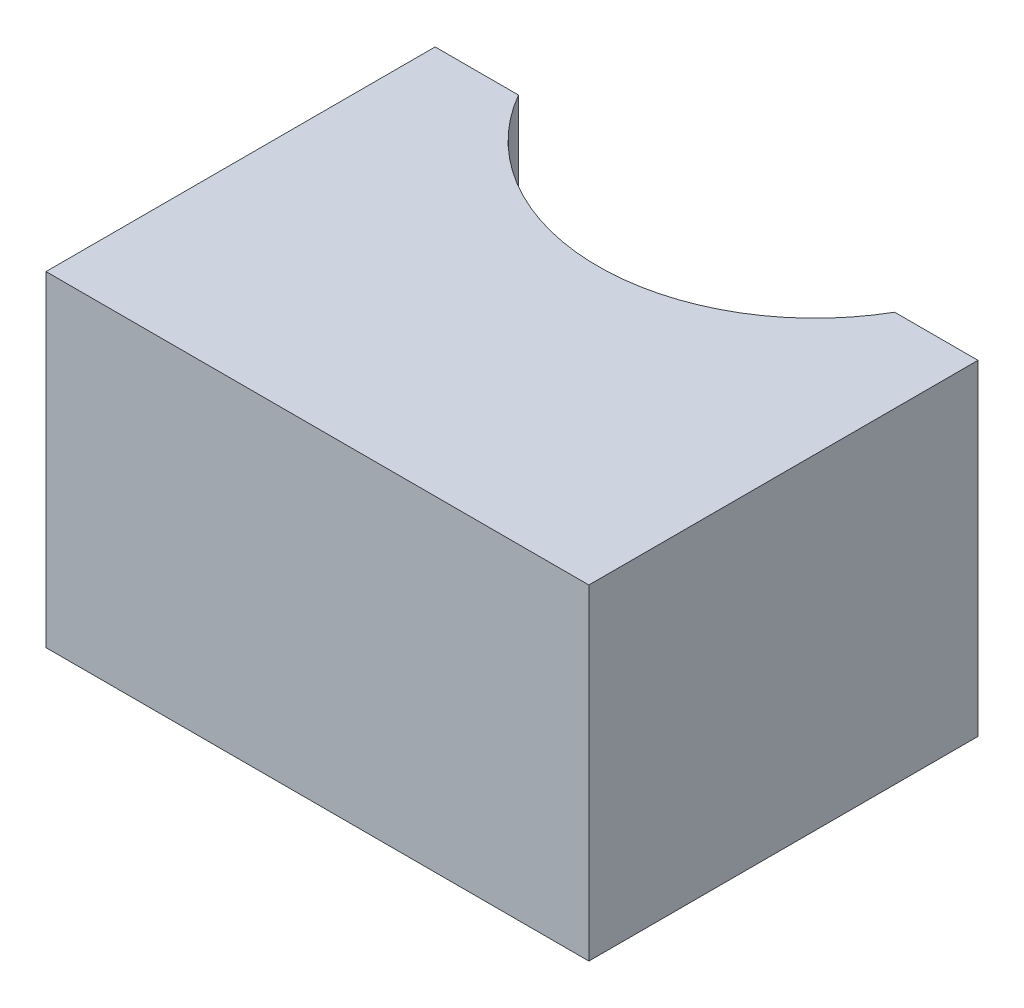
SolidWorks part; units mm, degrees
material "Custom Plastic"
ref_plane "X-Y Datum" through (0, 0, 0) normal (0, 0, 1) x (1, 0, 0)
ref_plane "X-Z Datum" through (0, 0, 0) normal (0, 1, 0) x (1, 0, 0)
ref_plane "Y-Z Datum" through (0, 0, 0) normal (1, 0, 0) x (0, 0, -1)
sketch "Sketch1" plane through (0, 0, 0) normal (0, 0, 1) x (1, 0, 0)
  line L1 (-15.875, 9.525) -> (15.875, 9.525)
  line L2 (-15.875, 9.525) -> (-15.875, -9.525)
  line L3 (-15.875, -9.525) -> (15.875, -9.525)
  line L4 (15.875, 9.525) -> (15.875, -9.525)
  line L5 (-15.875, 9.525) -> (15.875, -9.525) construction
  line L6 (-15.875, -9.525) -> (15.875, 9.525) construction
  point P0 (0, 0)
  dimension "D1" = 31.75
  dimension "D2" = 19.05
extrude "Boss-Extrude1" add sketch "Sketch1" along normal blind 22.7584
sketch "Sketch2" plane through (0, 9.525, 0) normal (0, 1, 0) x (1, 0, 0)
  circle A0 centre (0, 6.35) radius 12.7
  point P2 (0, -6.35)
  dimension "D1" = 25.4
  dimension "D2" = 6.35
extrude "Cut-Extrude1" cut sketch "Sketch2" against normal through all
